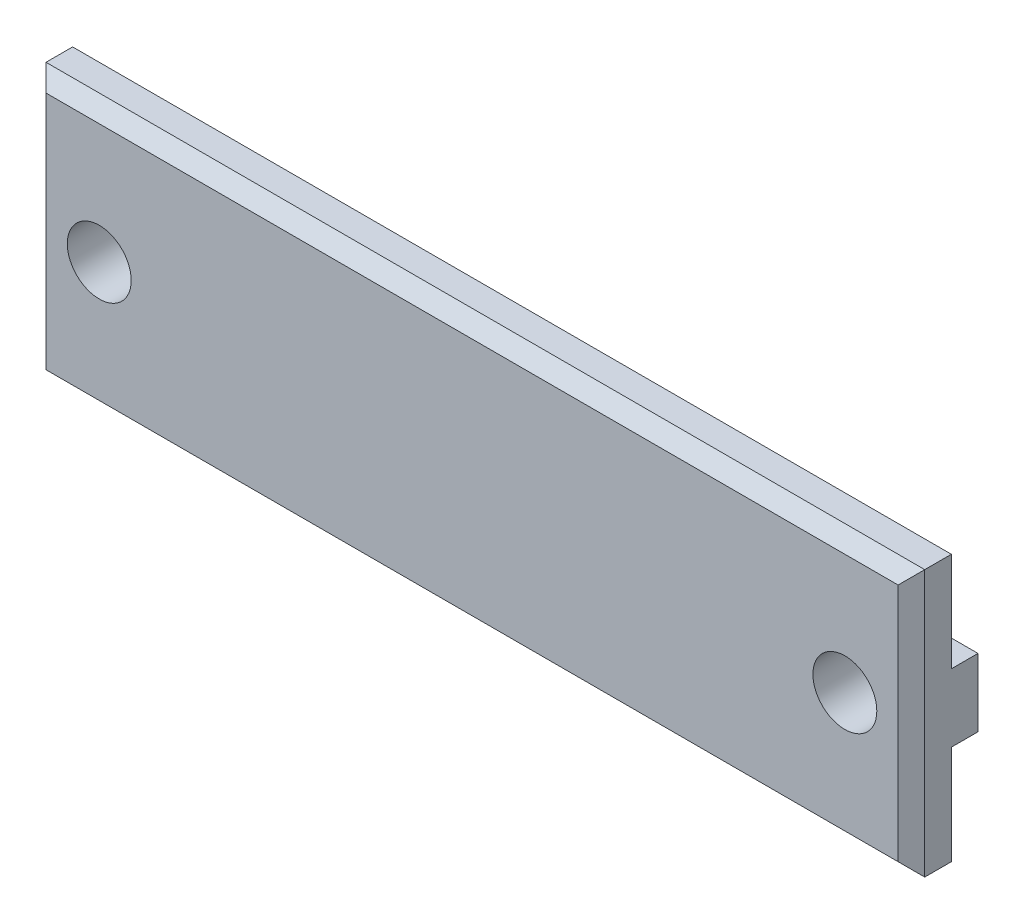
SolidWorks part; units mm, degrees
ref_plane "정면" through (0, 0, 0) normal (0, 0, 1) x (1, 0, 0)
ref_plane "윗면" through (0, 0, 0) normal (0, 1, 0) x (1, 0, 0)
ref_plane "우측면" through (0, 0, 0) normal (1, 0, 0) x (0, 0, -1)
sketch "스케치1" plane through (0, 0, 0) normal (0, 0, 1) x (1, 0, 0)
  line L0 (23, 2.55) -> (33, 2.55)
  line L1 (-33, 2.55) -> (-23, 2.55)
  line L2 (-33, 2.55) -> (-33, -2.55)
  line L3 (-33, -2.55) -> (-23, -2.55)
  line L4 (-23, 2.55) -> (-23, -2.55)
  line L5 (-33, 2.55) -> (-23, -2.55) construction
  line L6 (-33, -2.55) -> (-23, 2.55) construction
  line L7 (23, 2.55) -> (23, -2.55)
  line L8 (23, -2.55) -> (33, -2.55)
  line L9 (33, 2.55) -> (33, -2.55)
  line L10 (23, 2.55) -> (33, -2.55) construction
  line L11 (23, -2.55) -> (33, 2.55) construction
  point P0 (-28, 0)
  point P7 (28, 0)
  dimension "D1" = 5.1
  dimension "D2" = 5.1
  dimension "D3" = 23
  dimension "D4" = 23
  dimension "D5" = 10
  dimension "D6" = 10
extrude "보스-돌출1" add sketch "스케치1" along normal blind 2
sketch "스케치2" plane through (0, 0, 2) normal (0, 0, 1) x (1, 0, 0)
  line L0 (-33, 2.55) -> (-33, -2.55) construction
  line L1 (-33, 10) -> (33, 10)
  line L2 (-33, 10) -> (-33, -10)
  line L3 (-33, -10) -> (33, -10)
  line L4 (33, 10) -> (33, -10)
  line L5 (33, -2.55) -> (33, 2.55) construction
  dimension "D1" = 20
  dimension "D2" = 10
extrude "보스-돌출2" add sketch "스케치2" along normal blind 3
hole_wizard "M4 여유 구멍1" positions "스케치3" profile "스케치4" hole size "M4" standard "KS" end condition through all
sketch "스케치3" plane through (0, 0, 5) normal (0, 0, 1) x (1, 0, 0)
  line L0 (-33, 10) -> (-33, -10) construction
  line L1 (33, -10) -> (33, 10) construction
  line L2 (-33, -10) -> (33, -10) construction
  point P0 (-28, 0)
  point P2 (28, 0)
  dimension "D1" = 5
  dimension "D2" = 5
  dimension "D3" = 10
  dimension "D4" = 10
sketch "스케치4" plane through (-28, 0, 5) normal (1, 0, 0) x (0, -1, 0)
  line L0 (0, 0) -> (0, 5)
  line L1 (0, 5) -> (2.4, 5)
  line L2 (2.4, 5) -> (2.4, 0)
  line L5 (2.4, 0) -> (0, 0)
  line L11 (0, -6.35) -> (0, 107.95) construction
  dimension "관통 구멍 지름" = 4.8
  dimension "관통 구멍 깊이" = 5
chamfer "모따기1" distance 1 angle 45 4 edges at (0, 10, 5) (33, 0, 5) (0, -10, 5) (-33, 0, 5)
